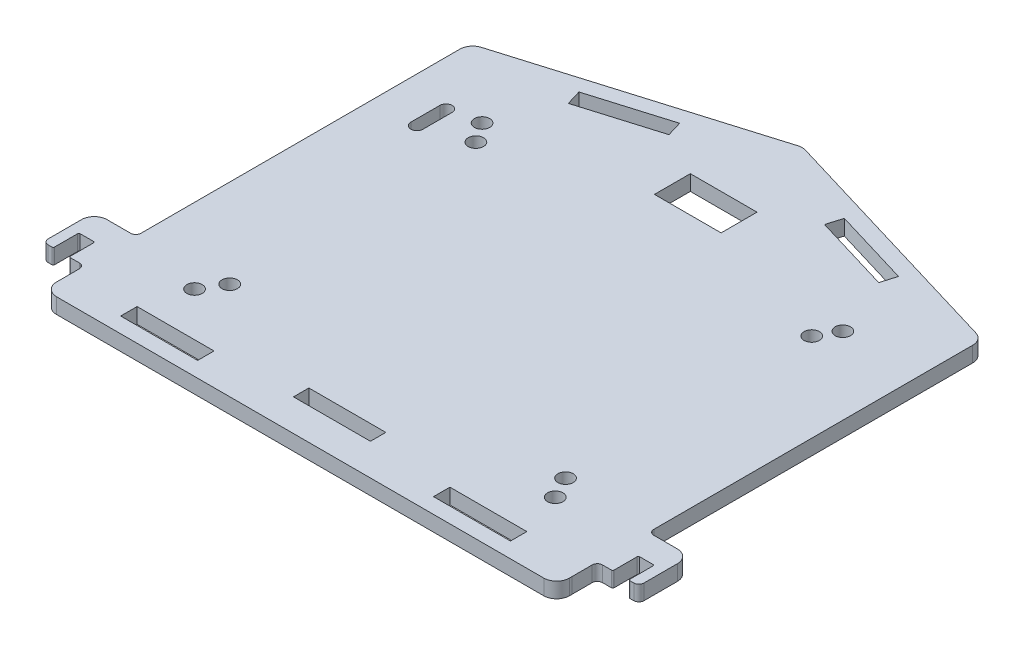
SolidWorks part; units mm, degrees
ref_plane "Alzado" through (0, 0, 0) normal (0, 0, 1) x (1, 0, 0)
ref_plane "Planta" through (0, 0, 0) normal (0, 1, 0) x (1, 0, 0)
ref_plane "Vista lateral" through (0, 0, 0) normal (1, 0, 0) x (0, 0, -1)
sketch "Croquis3" plane through (0, 0, 0) normal (0, 1, 0) x (1, 0, 0)
  line L0 (-23.5, 40) -> (23.5, 40) construction
  line L3 (-50, -40) -> (50, -40)
  line L5 (-50, 40) -> (50, -40) construction
  line L6 (-50, -40) -> (50, 40) construction
  line L7 (-48.2184, 40.5345) -> (-0.7184, 54.7845)
  line L8 (0.7184, 54.7845) -> (48.2184, 40.5345)
  line L9 (23.5, 40) -> (23.5, -32) construction
  line L14 (23.5, -32) -> (-23.5, -32) construction
  line L16 (-23.5, -32) -> (-23.5, 40) construction
  line L17 (0, 7.5742) -> (0, -7.5742) construction
  line L18 (-8.1342, 0) -> (8.1342, 0) construction
  line L19 (-24.4684, 47.6595) -> (-23.6063, 44.786) construction
  line L20 (-31.1563, 42.521) -> (-16.0563, 47.051)
  line L21 (-16.0563, 47.051) -> (-15.1655, 44.0817)
  line L28 (-15.1655, 44.0817) -> (-30.2655, 39.5517)
  line L29 (-30.2655, 39.5517) -> (-31.1563, 42.521)
  line L30 (15.1655, 44.0817) -> (30.2655, 39.5517)
  line L31 (16.0563, 47.051) -> (15.1655, 44.0817)
  line L32 (31.1563, 42.521) -> (16.0563, 47.051)
  line L33 (30.2655, 39.5517) -> (31.1563, 42.521)
  line L34 (-50, -35.05) -> (-53, -35.05)
  line L35 (-53, -35.05) -> (-53, -30.05)
  line L36 (-53, -30.05) -> (-56.1, -30.05)
  line L37 (-56.1, -30.05) -> (-56.1, -35.05)
  line L38 (-56.1, -35.05) -> (-58.1, -35.05)
  line L39 (-58.1, -35.05) -> (-58.1, -27.55)
  line L40 (-55.6, -25.05) -> (-50, -25.05)
  line L41 (-50, -40) -> (-50, -35.05)
  line L42 (-50, -25.05) -> (-50, 38.1399)
  line L43 (50, -25.05) -> (50, 38.1399)
  line L44 (55.6, -25.05) -> (50, -25.05)
  line L45 (58.1, -35.05) -> (58.1, -27.55)
  line L46 (56.1, -30.05) -> (56.1, -35.05)
  line L47 (53, -30.05) -> (56.1, -30.05)
  line L48 (53, -35.05) -> (53, -30.05)
  line L49 (50, -35.05) -> (53, -35.05)
  line L50 (50, -40) -> (50, -35.05)
  line L51 (56.1, -35.05) -> (58.1, -35.05)
  arc A4 (48.2184, 40.5345) -> (50, 38.1399) centre (47.5, 38.1399) cw
  arc A5 (-48.2184, 40.5345) -> (-50, 38.1399) centre (-47.5, 38.1399) ccw
  arc A6 (0.7184, 54.7845) -> (-0.7184, 54.7845) centre (0, 52.3899) ccw
  arc A7 (-58.1, -27.55) -> (-55.6, -25.05) centre (-55.6, -27.55) cw
  arc A8 (58.1, -27.55) -> (55.6, -25.05) centre (55.6, -27.55) ccw
  point P0 (0, 0)
  point P6 (-31.5, 45.55)
  point P11 (0, 40)
  point P16 (0, 0)
  point P18 (0, 0)
  point P21 (-0.0334, 37.8306)
  point P25 (-23.6063, 44.786)
  point P26 (21.4666, 4.1883)
  point P29 (0, 0)
  point P37 (-50, -35.05)
  point P39 (29, 0)
  point P53 (0, 55)
  point P58 (-58.1, -25.05)
  dimension "D7" = 3
  dimension "D8" = 15.1
  dimension "D10" = 4.95
  dimension "D11" = 10
  dimension "D17" = 2.5
  dimension "D20" = 2.5
  dimension "D1" = 80
  dimension "D2" = 100
  dimension "D3" = 47
  dimension "D4" = 72
  dimension "D5" = 15
  dimension "D6" = 18.5
  dimension "D9" = 3.1
  dimension "D14" = 5
  dimension "D15" = 5
  dimension "D16" = 2
  dimension "D18" = 3.1
  dimension "D19" = 3
extrude "Saliente-Extruir1" add sketch "Croquis3" along normal blind 3
sketch "Croquis4" plane through (0, 3, 0) normal (0, 1, 0) x (1, 0, 0)
  line L12 (-32.7367, 7.5) -> (-32.7367, 24) construction
  line L14 (-8.1155, 0) -> (8.1155, 0) construction
  line L16 (-38, -40) -> (-23, -40)
  line L18 (-38, -40) -> (-38, -36.8)
  line L19 (-38, -36.8) -> (-23, -36.8)
  line L20 (-23, -40) -> (-23, -36.8)
  line L24 (38, -36.8) -> (23, -36.8)
  line L25 (23, -40) -> (23, -36.8)
  line L26 (38, -40) -> (23, -40)
  line L27 (38, -40) -> (38, -36.8)
  line L28 (0, -36.8) -> (0, 0) construction
  line L39 (-7.5, -36.8) -> (7.5, -36.8)
  line L40 (7.5, -36.8) -> (7.5, -33.8)
  line L41 (-41.2608, 26.6984) -> (-41.2608, 21.0303) construction
  line L44 (-40.0697, 26.6984) -> (-40.0697, 21.0303)
  line L45 (-42.452, 26.6984) -> (-42.452, 21.0303)
  line L51 (7.5, -33.8) -> (-7.5, -33.8)
  line L52 (-7.5, -33.8) -> (-7.5, -36.8)
  circle A1 centre (32.75, 24) radius 1.5
  circle A2 centre (-32.7367, 24) radius 1.5
  circle A3 centre (32.75, -24) radius 1.5
  circle A4 centre (-32.7367, -24) radius 1.5
  arc A7 (-40.0697, 26.6984) -> (-42.452, 26.6984) centre (-41.2608, 26.6984) ccw
  arc A8 (-42.452, 21.0303) -> (-40.0697, 21.0303) centre (-41.2608, 21.0303) ccw
  point P2 (0, 0)
  point P6 (0, -36.8)
  point P11 (0, 0)
  point P19 (-41.2608, 23.8644)
  point P23 (0, 0)
  point P29 (-38, -40)
  dimension "D4" = 3
  dimension "D6" = 3.2
  dimension "D9" = 3
  dimension "D1" = 3
  dimension "D2" = 15
  dimension "D3" = 16.5
  dimension "D7" = 15
extrude "Cortar-Extruir1" cut sketch "Croquis4" against normal mid plane 6
sketch "Croquis5" plane through (0, 0, 0) normal (0, 1, 0) x (1, 0, 0)
  line L1 (-50, -40) -> (49.9993, -40)
  line L2 (-50, -40) -> (-50, -40.5)
  line L3 (-47.5, -43) -> (47.4993, -43)
  line L4 (49.9993, -40) -> (49.9993, -40.5)
  arc A0 (47.4993, -43) -> (49.9993, -40.5) centre (47.4993, -40.5) ccw
  arc A1 (-50, -40.5) -> (-47.5, -43) centre (-47.5, -40.5) ccw
  point P7 (49.9993, -43)
  point P10 (-50, -43)
  dimension "D3" = 2.5
  dimension "D1" = 99.9993
  dimension "D2" = 3
extrude "Saliente-Extruir2" add sketch "Croquis5" along normal blind 3
fillet "Redondeo1" radius 1 6 edges at (50, 1.5, 25.05) (50, 1.5, 35.05) (58.1, 1.5, 35.05) (-50, 1.5, 25.05) (-58.1, 1.5, 35.05) (-50, 1.5, 35.05)
fillet "Redondeo2" radius 0.25 8 edges at (56.1, 1.5, 30.05) (56.1, 1.5, 35.05) (53, 1.5, 30.05) (53, 1.5, 35.05) (-56.1, 1.5, 35.05) (-53, 1.5, 35.05) (-53, 1.5, 30.05) (-56.1, 1.5, 30.05)
sketch "Croquis6" plane through (0, 3, 0) normal (0, 1, 0) x (1, 0, 0)
  line L0 (-34.4778, 28.8482) -> (34.5222, 28.8482) construction
  line L1 (0, 0) -> (0, 32.5814) construction
  line L6 (-6.5, 32.5814) -> (6.5, 32.5814)
  line L7 (6.5, 32.5814) -> (6.5, 39.5814)
  line L8 (6.5, 39.5814) -> (-6.5, 39.5814)
  line L9 (-6.5, 39.5814) -> (-6.5, 32.5814)
  circle A4 centre (-35.3612, 27.8339) radius 1.5
  circle A5 centre (34.9779, 27.8339) radius 1.5
  circle A6 centre (34.9779, -28.2345) radius 1.5
  circle A7 centre (-35.3612, -28.2345) radius 1.5
  point P16 (0, 32.5814)
  dimension "D1" = 7
  dimension "D2" = 13
extrude "Cortar-Extruir2" cut sketch "Croquis6" against normal mid plane 10
